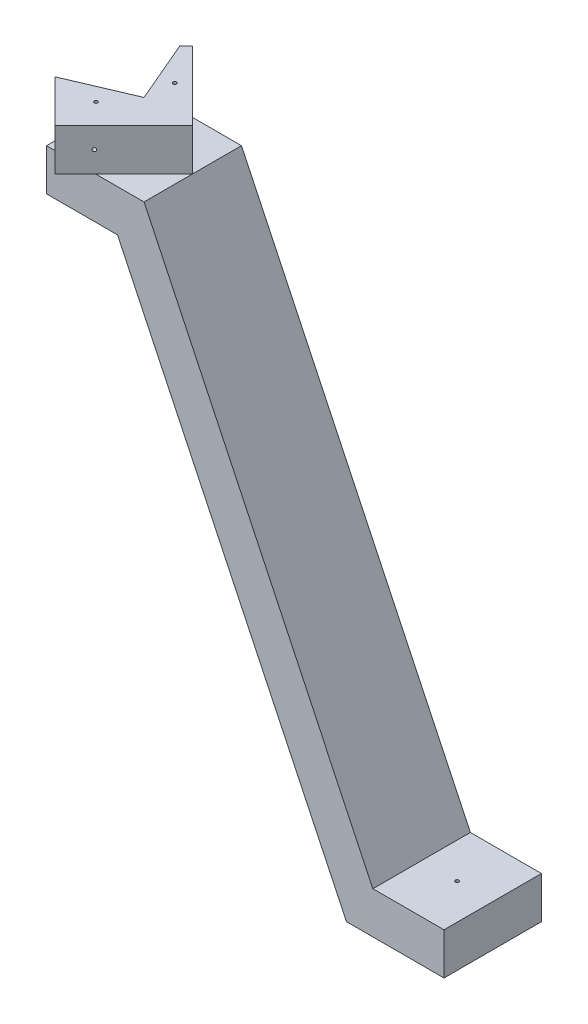
SolidWorks part; units mm, degrees
ref_plane "Frontal Plane" through (0, 0, 0) normal (0, 0, 1) x (1, 0, 0)
ref_plane "Horizontal Plane" through (0, 0, 0) normal (0, 1, 0) x (1, 0, 0)
ref_plane "Profile Plane" through (0, 0, 0) normal (1, 0, 0) x (0, 0, -1)
sketch "Sketch1" plane through (0, 0, 0) normal (0, 0, 1) x (1, 0, 0)
  line L0 (0, 0) -> (-208.7981, 438.15)
  line L2 (-184.7495, 476.25) -> (24.0487, 38.1)
  line L3 (24.0487, 38.1) -> (88.9, 38.1)
  line L4 (88.9, 38.1) -> (88.9, 0)
  line L5 (88.9, 0) -> (0, 0)
  line L6 (-184.7495, 476.25) -> (-273.6495, 476.25)
  line L7 (-273.6495, 476.25) -> (-273.6495, 438.15)
  line L8 (-273.6495, 438.15) -> (-208.7981, 438.15)
  point P7 (-229.1995, 476.25)
  point P9 (56.4743, 38.1)
  dimension "D1" = 38.1
  dimension "D2" = 88.9
  dimension "D3" = 285.6738
  dimension "D4" = 438.15
  dimension "D5" = 88.9
  dimension "D6" = 38.1
extrude "Boss-Extrude1" add sketch "Sketch1" along normal mid plane 88.9
hole_wizard "1/8 (0.125) Diameter Hole1" positions "3DSketch1" profile "Sketch3" hole size "1/8" standard "ANSI Inch" end condition through all
sketch3d "3DSketch1"
  line L0 (88.9, 38.1, -44.45) -> (24.0487, 38.1, -44.45) construction
  line L3 (56.4743, 38.1, -44.45) -> (56.4743, 38.1, 54.3509) construction
  point P0 (56.4743, 38.1, 0)
  dimension "D1" = 44.45
sketch "Sketch3" plane through (56.4743, 38.1, 0) normal (1, 0, 0) x (0, 0, 1)
  line L0 (0, 0) -> (0, 38.1)
  line L1 (0, 38.1) -> (1.5875, 38.1)
  line L2 (1.5875, 38.1) -> (1.5875, 0)
  line L5 (1.5875, 0) -> (0, 0)
  line L11 (0, -6.35) -> (0, 107.95) construction
  dimension "Thru Hole Dia." = 3.175
  dimension "Thru Hole Depth" = 38.1
sketch "Sketch4" plane through (0, 476.25, 0) normal (0, 1, 0) x (1, 0, 0)
  line L0 (-247.6113, 62.8618) -> (-184.7495, 0)
  line L1 (-184.7495, 0) -> (-247.6113, -62.8618)
  line L3 (-247.6113, -62.8618) -> (-310.4731, 0)
  line L4 (-310.4731, 0) -> (-247.6113, 62.8618)
  line L7 (-184.7495, 44.45) -> (-273.6495, 44.45) construction
  line L8 (-273.6495, -44.45) -> (-273.6495, 44.45) construction
  dimension "D1" = 90
  dimension "D3" = 88.9
  dimension "D4" = 44.45
  dimension "D5" = 88.9
extrude "Boss-Extrude2" add sketch "Sketch4" along normal blind 38.1
sketch "Sketch6" plane through (0, 438.15, 0) normal (0, -1, 0) x (1, 0, 0)
  line L0 (-310.4731, 34.698) -> (-229.1995, 0)
  line L1 (-229.1995, 0) -> (-310.4731, -190.3683)
  line L5 (-273.6495, 36.8236) -> (-273.6495, -36.8236) construction
  line L6 (-310.4731, 34.698) -> (-310.4731, -190.3683)
  line L7 (-273.6495, -44.45) -> (-208.7981, -44.45) construction
  line L9 (-229.1995, 0) -> (-344.6209, 0) construction
  dimension "D1" = 44.45
  dimension "D2" = 44.45
  dimension "D3" = 66.881
  dimension "D4" = 115.4214
  dimension "D5" = 23.119
extrude "Cut-Extrude1" cut sketch "Sketch6" against normal through all both and the other way through all
hole_wizard "1/8 (0.125) Diameter Hole2" positions "Sketch7" profile "Sketch8" hole size "1/8" standard "ANSI Inch" end condition through all
sketch "Sketch7" plane through (-92.3747, 0, -92.3747) normal (0.7071, 0, 0.7071) x (0.7071, 0, -0.7071)
  line L0 (-219.5376, 514.35) -> (-219.5376, 476.25) construction
  line L1 (-219.5376, 476.25) -> (-193.4994, 476.25) construction
  point P0 (-194.1376, 495.3)
  dimension "D1" = 25.4
  dimension "D2" = 19.05
sketch "Sketch8" plane through (-229.6508, 495.3, 44.9013) normal (0, 1, 0) x (0.7071, 0, -0.7071)
  line L0 (0, 0) -> (0, 116.1556)
  line L1 (0, 116.1556) -> (1.5875, 116.1556)
  line L2 (1.5875, 116.1556) -> (1.5875, 0)
  line L5 (1.5875, 0) -> (0, 0)
  line L11 (0, -6.35) -> (0, 107.95) construction
  dimension "Thru Hole Dia." = 3.175
  dimension "Thru Hole Depth" = 116.1556
hole_wizard "1/8 (0.125) Diameter Hole3" positions "Sketch9" profile "Sketch10" hole size "1/8" standard "ANSI Inch" end condition through all
sketch "Sketch9" plane through (-92.3747, 0, 92.3747) normal (0.7071, 0, -0.7071) x (-0.7071, 0, -0.7071)
  line L0 (219.5376, 514.35) -> (219.5376, 476.25) construction
  line L1 (193.4994, 476.25) -> (219.5376, 476.25) construction
  point P0 (194.1376, 495.3)
  dimension "D1" = 25.4
  dimension "D2" = 19.05
sketch "Sketch10" plane through (-229.6508, 495.3, -44.9013) normal (0, 1, 0) x (-0.7071, 0, -0.7071)
  line L0 (0, 0) -> (0, 116.1556)
  line L1 (0, 116.1556) -> (1.5875, 116.1556)
  line L2 (1.5875, 116.1556) -> (1.5875, 0)
  line L5 (1.5875, 0) -> (0, 0)
  line L11 (0, -6.35) -> (0, 107.95) construction
  dimension "Thru Hole Dia." = 3.175
  dimension "Thru Hole Depth" = 116.1556
hole_wizard "1/8 (0.125) Diameter Hole4" positions "Sketch11" profile "Sketch12" hole size "1/8" standard "ANSI Inch" end condition through all
sketch "Sketch11" plane through (0, 438.15, 0) normal (0, -1, 0) x (-1, 0, 0)
  line L0 (229.1995, -44.45) -> (266.0231, -44.45) construction
  line L2 (248.1764, 44.45) -> (208.7981, 44.45) construction
  line L3 (208.7981, -44.45) -> (208.7981, 44.45) construction
  point P0 (247.6113, -25.4)
  point P2 (226.5781, 25.4)
  dimension "D1" = 19.05
  dimension "D2" = 19.05
  dimension "D3" = 17.78
sketch "Sketch12" plane through (-247.6113, 438.15, 25.4) normal (1, 0, 0) x (0, 0, -1)
  line L0 (0, 0) -> (0, 76.2)
  line L1 (0, 76.2) -> (1.5875, 76.2)
  line L2 (1.5875, 76.2) -> (1.5875, 0)
  line L5 (1.5875, 0) -> (0, 0)
  line L11 (0, -6.35) -> (0, 107.95) construction
  dimension "Thru Hole Dia." = 3.175
  dimension "Thru Hole Depth" = 76.2
